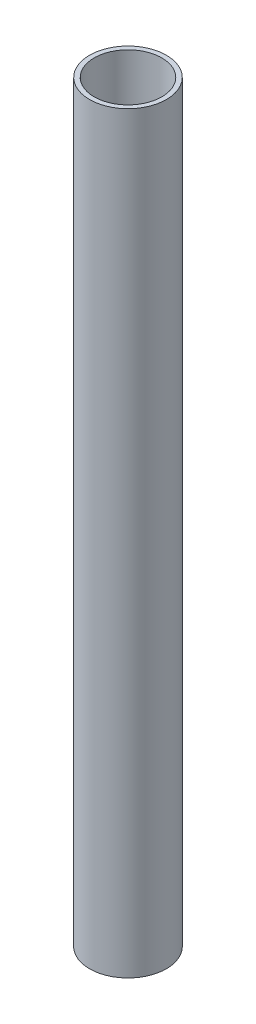
SolidWorks part; units mm, degrees
material "Thornel Mat VMA"
ref_plane "前视基准面" through (0, 0, 0) normal (0, 0, 1) x (1, 0, 0)
ref_plane "上视基准面" through (0, 0, 0) normal (0, 1, 0) x (1, 0, 0)
ref_plane "右视基准面" through (0, 0, 0) normal (1, 0, 0) x (0, 0, -1)
sketch "草图1" plane through (0, 0, 0) normal (0, 1, 0) x (1, 0, 0)
  circle A0 centre (0, 0) radius 11
  circle A1 centre (0, 0) radius 12.5
  dimension "D1" = 25
  dimension "D2" = 22
extrude "凸台-拉伸1" add sketch "草图1" along normal blind 245
